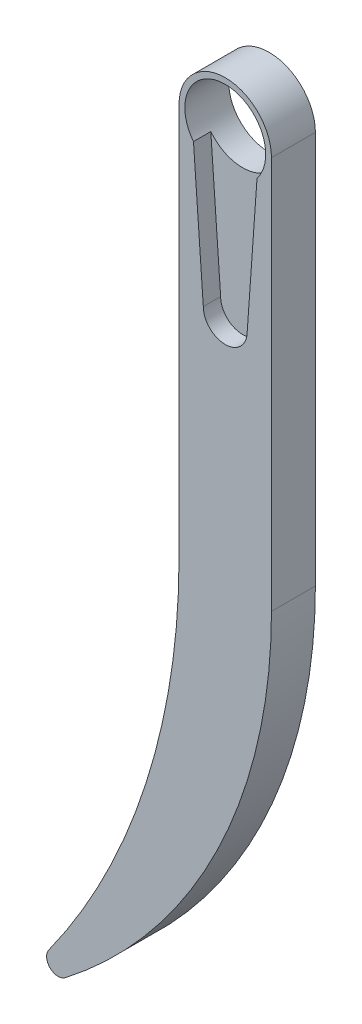
SolidWorks part; units mm, degrees
ref_plane "Piano frontale" through (0, 0, 0) normal (0, 0, 1) x (1, 0, 0)
ref_plane "Piano superiore" through (0, 0, 0) normal (0, 1, 0) x (1, 0, 0)
ref_plane "Piano destro" through (0, 0, 0) normal (1, 0, 0) x (0, 0, -1)
sketch "Schizzo1" plane through (0, 0, 0) normal (0, 0, 1) x (1, 0, 0)
  line L0 (0, 0) -> (0, 80) construction
  line L1 (-4, 0) -> (-4, 80)
  line L2 (4, 0) -> (4, 80)
  arc A0 (-4, 0) -> (4, 0) centre (0, 0) ccw
  arc A1 (4, 80) -> (-4, 80) centre (0, 80) ccw
  circle A2 centre (0, 80) radius 1.8979
  point P3 (0, 40)
  dimension "D1" = 4
  dimension "D2" = 80
extrude "Estrusione-Estrusione1" add sketch "Schizzo1" along normal blind 3.8
sketch "Schizzo7" plane through (0, 0, 3.8) normal (0, 0, 1) x (1, 0, 0)
  line L0 (-4, 46) -> (4, 46)
  line L3 (4, 46) -> (4, -4)
  line L4 (4, -4) -> (-4, -4)
  line L5 (-4, -4) -> (-4, 46)
  line L6 (4, 0) -> (4, 80) construction
  line L7 (-4, 80) -> (-4, 0) construction
  arc A0 (-4, 0) -> (4, 0) centre (0, 0) ccw construction
  dimension "D1" = 50
extrude "Taglio-Estrusione4" cut sketch "Schizzo7" against normal up to surface (3.8 mm away) up to face at (0, 40, 0)
sketch "Schizzo9" plane through (0, 0, 3.8) normal (0, 0, 1) x (1, 0, 0)
  line L0 (-64, 46) -> (-4, 46) construction
  line L1 (4, 46) -> (-4, 46) construction
  line L2 (-4, 80) -> (-4, 46) construction
  line L3 (-4, 46) -> (4, 46)
  line L4 (-4, 46) -> (-4, 6) construction
  arc A0 (-19.2786, 6) -> (-4, 46) centre (-64, 46) ccw
  arc A1 (-4, 14) -> (4, 46) centre (-64, 46) ccw construction
  arc A2 (-19.2786, 6) -> (4, 46) centre (-42.0056, 46) ccw
  dimension "D1" = 120
  dimension "D2" = 40
extrude "Estrusione-Estrusione4" add sketch "Schizzo9" against normal up to surface (3.8 mm away) up to face at (0, 64, 0)
fillet "Raccordo2" radius 1 1 edges at (-19.2786, 6, 1.9)
sketch "Schizzo10" plane through (0, 0, 3.8) normal (0, 0, 1) x (1, 0, 0)
  circle A0 centre (0, 80) radius 3.5
  arc A2 (4, 80) -> (-4, 80) centre (0, 80) ccw construction
  dimension "D1" = 7
extrude "Taglio-Estrusione5" cut sketch "Schizzo10" against normal blind 10
sketch "Schizzo13" plane through (0, 0, 3.8) normal (0, 0, 1) x (1, 0, 0)
  line L2 (-2.75, 77.8349) -> (-1.9, 65.9)
  line L3 (1.9, 65.9) -> (2.75, 77.8349)
  line L4 (-2.75, 77.8349) -> (-1.9, 65.9)
  line L5 (1.9, 65.9) -> (2.75, 77.8349)
  arc A3 (-3.5, 80) -> (-2.75, 77.8349) centre (0, 80) ccw
  arc A4 (-1.9, 65.9) -> (1.9, 65.9) centre (0, 65.9) ccw
  arc A5 (2.75, 77.8349) -> (-3.5, 80) centre (0, 80) ccw
  arc A6 (-3.5, 80) -> (-2.75, 77.8349) centre (0, 80) ccw
  arc A7 (-1.9, 65.9) -> (1.9, 65.9) centre (0, 65.9) ccw
  arc A8 (2.75, 77.8349) -> (-3.5, 80) centre (0, 80) ccw
  dimension "D1" = 0
extrude "Taglio-Estrusione6" cut sketch "Schizzo13" against normal blind 1.5
